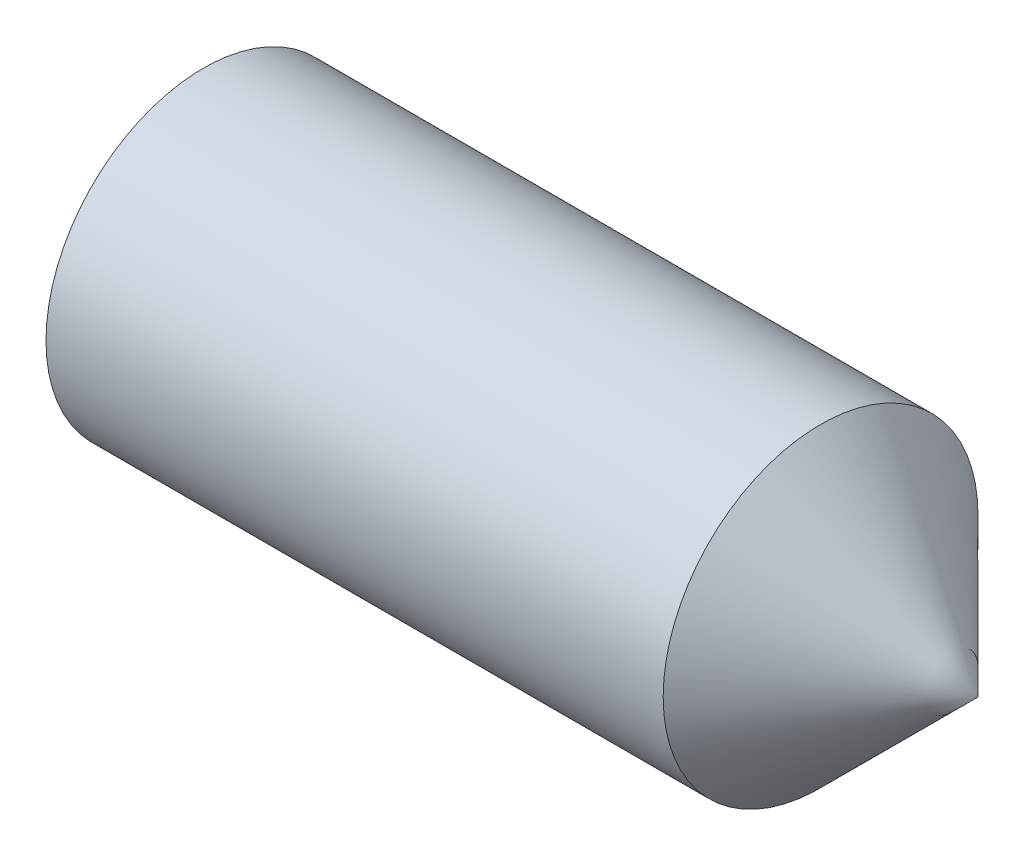
SolidWorks part; units mm, degrees
revolve "BaseBody" add sketch "BodySke" angle 360 about L5
sketch "BodySke" plane through (0, 0, 0) normal (0, 0, 1) x (1, 0, 0)
  line L0 (0, 0) -> (0, 10.352)
  line L1 (0, 10.352) -> (0.9515, 12)
  line L2 (0.9515, 12) -> (48, 12)
  line L3 (48, 12) -> (60, 0)
  line L4 (60, 0) -> (0, 0)
  line L5 (-12.7, 0) -> (88.9, 0) construction
  line L6 (48, -12) -> (60, 0) construction
  line L7 (1.5, 15.875) -> (1.5, -3.175) construction
  line L8 (0, -10.352) -> (0.9515, -12) construction
  dimension "Diameter" = 24
  dimension "Drive_ch_ang" = 60
  dimension "Minor_dia" = 20.704
  dimension "Advance" = 3
  dimension "Cone_ang" = 90
  dimension "Length" = 60
cosmetic thread "ThreadCosmetic" [suppressed] parameters "Thread_minor"=20.704
ref_plane "Plane1" through (0, 0, 0) normal (0, 0, 1) x (1, 0, 0)
ref_plane "Plane2" through (0, 0, 0) normal (0, 1, 0) x (1, 0, 0)
ref_plane "Plane3" through (0, 0, 0) normal (1, 0, 0) x (0, 0, -1)
sketch "Sketch2" plane through (0, 0, 0) normal (-1, 0, 0) x (0, 0, 1)
  line L0 (3.4641, 6) -> (-3.4641, 6)
  line L1 (-3.4641, 6) -> (-6.9282, 0)
  line L2 (3.4641, 6) -> (6.9282, 0)
  line L3 (3.4641, -6) -> (6.9282, 0)
  line L4 (3.4641, -6) -> (-3.4641, -6)
  line L5 (-3.4641, -6) -> (-6.9282, 0)
  dimension "Hex_size" = 12
  dimension "D2" = 6
  dimension "D3" = 6
extrude "Hex" cut sketch "Sketch2" against normal blind 15
sketch "ThdSchSke" plane through (0, 0, 0) normal (0, 0, 1) x (1, 0, 0)
  line L0 (0.9515, -10.352) -> (-0.2025, -12)
  line L1 (0.9515, -10.352) -> (2.1054, -12)
  line L2 (2.1054, -12) -> (2.1054, -15)
  line L3 (-3.175, 0) -> (5.1513, 0) construction
  line L4 (0.9515, 12) -> (0.9515, -12) construction
  line L5 (2.1054, -15) -> (-0.2025, -15)
  line L6 (-0.2025, -15) -> (-0.2025, -12)
  dimension "Thread_minor" = 20.704
  dimension "Diameter" = 24
revolve "ThreadSchematic" [suppressed] cut sketch "ThdSchSke" angle 360 about L3
pattern_linear "ThdSchPat" [suppressed]
equation "\"D2@Sketch2\" = \"Hex_size@Sketch2\" / 2"
equation "\"D3@Sketch2\" = \"Hex_size@Sketch2\" / 2"
equation "\"Thread_minor@ThreadCosmetic\" = \"Minor_dia@BodySke\""
equation "\"Thread_minor@ThdSchSke\" = \"Thread_minor@ThreadCosmetic\""
equation "\"Diameter@ThdSchSke\" = \"Diameter@BodySke\""
equation "\"Overcut@ThdSchSke\" = \"Diameter@BodySke\" * 1.25"
equation "\"Num_threads@ThdSchPat\" = int( (\"Length@BodySke\" - ( ( ( \"Diameter@BodySke\" - \"Minor_dia@BodySke\" ) * 0.5 ) / tan( \"Drive_ch_ang@BodySke\" * 0.017453292 ) ) - ( ( \"Diameter@BodySke\" * 0.5 ) / tan( \"Cone_ang@BodySke\" * 0.008726646 ) ) ) / \"Advance@BodySke\" + 0.999 )  + 1"
equation "\"Advance@ThdSchPat\" = (\"Length@BodySke\" - ( ( ( \"Diameter@BodySke\" - \"Minor_dia@BodySke\" ) * 0.5 ) / tan( \"Drive_ch_ang@BodySke\" * 0.017453292 ) ) - ( ( \"Diameter@BodySke\" * 0.5 ) / tan( \"Cone_ang@BodySke\" * 0.008726646 ) ) ) /  (\"Num_threads@ThdSchPat\" - 1) 'relax it"
equation "' \"Num_threads@ThdSchPat\" = \"Num_threads@ThdSchPat\" - sgn( \"Num_threads@ThdSchPat\" - 1) '---chamfered tips only---"
